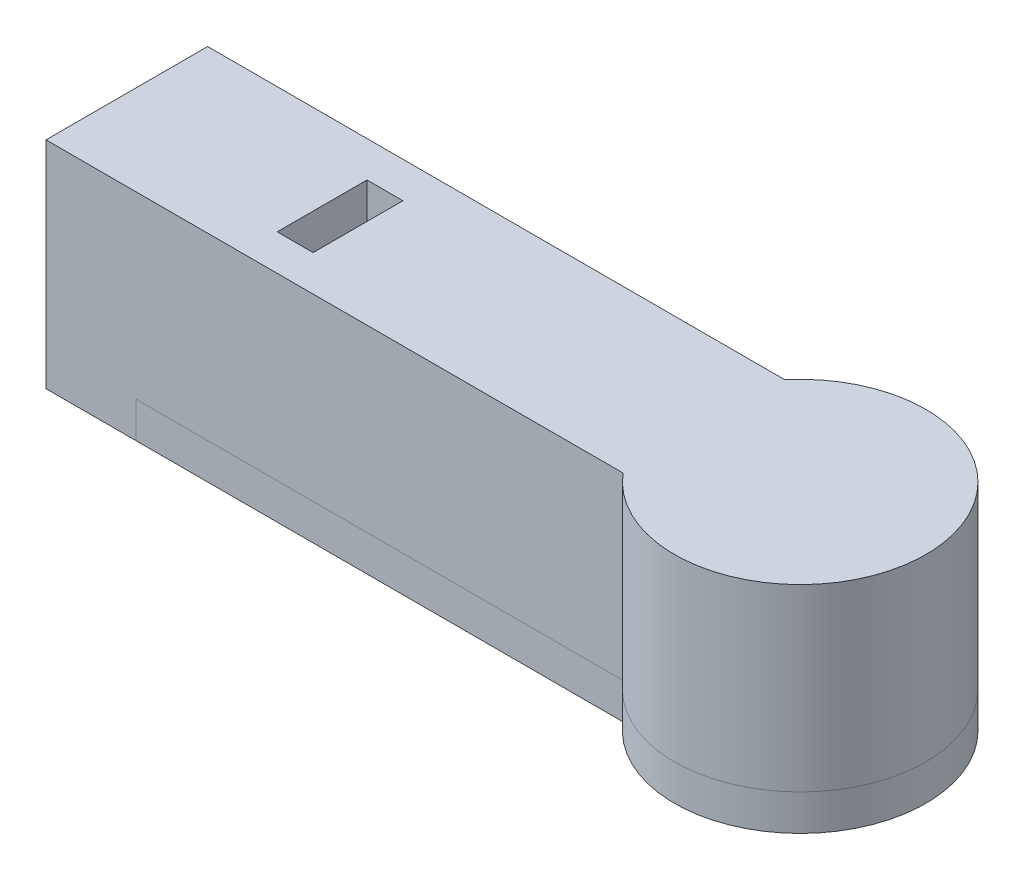
SolidWorks part; units mm, degrees
ref_plane "Front Plane" through (0, 0, 0) normal (0, 0, 1) x (1, 0, 0)
ref_plane "Top Plane" through (0, 0, 0) normal (0, 1, 0) x (1, 0, 0)
ref_plane "Right Plane" through (0, 0, 0) normal (1, 0, 0) x (0, 0, -1)
sketch "Sketch1" plane through (0, 0, 0) normal (0, 1, 0) x (1, 0, 0)
  line L1 (0, 3.401) -> (27.1296, 3.401)
  line L2 (0, 3.401) -> (0, -5.599)
  line L3 (0, -5.599) -> (27.1296, -5.599)
  arc A0 (27.1296, -5.599) -> (27.1296, 3.401) centre (32.4915, -1.099) ccw
  point P1 (0, -1.099)
  dimension "D3" = 14
  dimension "D2" = 9
extrude "Boss-Extrude1" add sketch "Sketch1" against normal blind 2
sketch "Sketch2" plane through (0, -2, 0) normal (0, -1, 0) x (1, 0, 0)
  line L1 (0, 5.599) -> (27.1296, 5.599)
  line L2 (0, 5.599) -> (0, -3.401)
  line L3 (0, -3.401) -> (27.1296, -3.401)
  line L5 (4, 3.599) -> (28.1613, 3.599)
  line L6 (4, 3.599) -> (4, -1.401)
  line L7 (4, -1.401) -> (28.1613, -1.401)
  arc A0 (27.1296, -3.401) -> (27.1296, 5.599) centre (32.4915, 1.099) ccw
  arc A1 (28.1613, -1.401) -> (28.1613, 3.599) centre (32.4915, 1.099) ccw
  dimension "D3" = 2
  dimension "D4" = 9
  dimension "7" = 7
  dimension "D1" = 2
  dimension "D2" = 4
  dimension "2" = 2
extrude "Boss-Extrude2" add sketch "Sketch2" along normal blind 8
sketch "Sketch3" plane through (0, 0, 0) normal (-1, 0, 0) x (0, 0, 1)
  line L0 (-3.401, 0) -> (-3.401, -10) construction
  line L2 (-3.401, 0) -> (5.599, 0) construction
  circle A0 centre (1.099, -5) radius 3
  point P6 (0, 0)
  point P7 (0, 0)
  point P8 (1.099, 0)
extrude "Cut-Extrude1" cut sketch "Sketch3" against normal blind 5
sketch "Sketch4" plane through (0, -2, 0) normal (0, -1, 0) x (1, 0, 0)
  line L0 (28.1613, 3.599) -> (4, 3.599) construction
  line L1 (5.8717, 3.599) -> (7.8717, 3.599)
  line L2 (5.8717, 3.599) -> (5.8717, -1.401)
  line L3 (5.8717, -1.401) -> (7.8717, -1.401)
  line L4 (7.8717, 3.599) -> (7.8717, -1.401)
  line L5 (4, -1.401) -> (28.1613, -1.401) construction
  dimension "D1" = 2
extrude "Cut-Extrude2" cut sketch "Sketch4" against normal blind 5
sketch "Sketch5" plane through (0, 0, 0) normal (-1, 0, 0) x (0, 0, 1)
  line L1 (-3.401, 0) -> (5.599, 0)
  line L2 (-3.401, 0) -> (-3.401, -12)
  line L3 (-3.401, -12) -> (5.599, -12)
  line L4 (5.599, 0) -> (5.599, -12)
  line L5 (-3.401, 0) -> (-3.401, -10) construction
  line L6 (5.599, -10) -> (5.599, 0) construction
  circle A6 centre (1.099, -5) radius 3
extrude "Boss-Extrude3" add sketch "Sketch5" along normal blind 5
sketch "Sketch6" plane through (0, -10, 0) normal (0, -1, 0) x (1, 0, 0)
  line L1 (0, 5.599) -> (27.1296, 5.599)
  line L2 (0, 5.599) -> (0, -3.401)
  line L3 (0, -3.401) -> (27.1296, -3.401)
  circle A0 centre (32.4915, 1.099) radius 3.5
  arc A1 (27.1296, -3.401) -> (27.1296, 5.599) centre (32.4915, 1.099) ccw
  dimension "D1" = 7
  dimension "D3" = 7
  dimension "D2" = 9
extrude "Boss-Extrude4" add sketch "Sketch6" along normal blind 2 separate body
